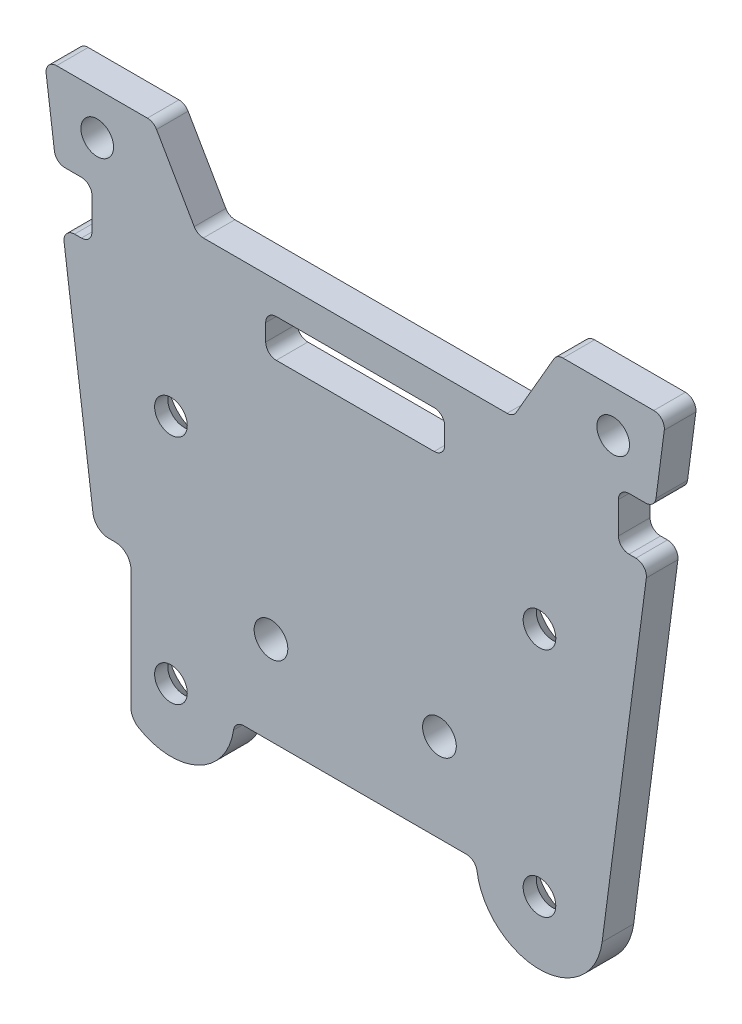
SolidWorks part; units mm, degrees
material "Thornel Mat VMA"
ref_plane "前视基准面" through (0, 0, 0) normal (0, 0, 1) x (1, 0, 0)
ref_plane "上视基准面" through (0, 0, 0) normal (0, 1, 0) x (1, 0, 0)
ref_plane "右视基准面" through (0, 0, 0) normal (1, 0, 0) x (0, 0, -1)
sketch "草图1" plane through (0, 0, 0) normal (0, 0, 1) x (1, 0, 0)
  line L0 (-37.3704, 16.5) -> (37.8879, 16.5) construction
  line L1 (29.5, -20.5) -> (18.6276, -20.5) construction
  line L2 (29.5, -20.5) -> (29.5, 20.5) construction
  line L3 (29.5, 20.5) -> (19.1569, 20.5)
  line L4 (-29.5, -20.5) -> (-29.5, 20.5) construction
  line L5 (29.5, -20.5) -> (-29.5, 20.5) construction
  line L6 (29.5, 20.5) -> (-29.5, -20.5) construction
  line L7 (0, 0) -> (16.279, 0) construction
  line L8 (-37.3704, -16.5) -> (37.8879, -16.5) construction
  line L9 (0, 0) -> (0, 13.3) construction
  line L10 (-18.6276, -20.5) -> (-29.5, -20.5) construction
  line L12 (-17.5, -24.9) -> (-17.5, -2.9) construction
  line L13 (29.5, 20.5) -> (23.4491, -25.6795)
  line L14 (-29.5, 20.5) -> (-23.4491, -25.6795)
  line L28 (-8.5, 10.3) -> (8.5, 10.3)
  line L37 (-19.1569, 20.5) -> (-15, 13.3)
  line L42 (-8.5, 10.3) -> (-8.5, 6.7)
  line L43 (-8.5, 6.7) -> (8.5, 6.7)
  line L44 (-15, 13.3) -> (15, 13.3)
  line L45 (15, 13.3) -> (19.1569, 20.5)
  line L46 (-19.1569, 20.5) -> (-29.5, 20.5)
  line L47 (11.5, -24.9) -> (-11.5, -24.9)
  line L48 (8.5, 10.3) -> (8.5, 6.7)
  line L49 (-8.5, 10.3) -> (8.5, 6.7) construction
  line L50 (-8.5, 6.7) -> (8.5, 10.3) construction
  circle A0 centre (-24.5, 16.5) radius 1.55
  circle A1 centre (-8, -16.5) radius 1.6
  circle A2 centre (8, -16.5) radius 1.6
  circle A3 centre (24.5, 16.5) radius 1.55
  circle A4 centre (-17.5, -24.9) radius 1.55
  circle A5 centre (17.5, -24.9) radius 1.55
  arc A7 (-23.4491, -25.6795) -> (-11.5, -24.9) centre (-17.5, -24.9) ccw
  circle A8 centre (-17.5, -2.9) radius 1.55
  circle A9 centre (17.5, -2.9) radius 1.55
  arc A10 (11.5, -24.9) -> (23.4491, -25.6795) centre (17.5, -24.9) ccw
  point P0 (0, 0)
  point P36 (0, 8.5)
  dimension "D3" = 16
  dimension "D5" = 3.1
  dimension "D6" = 3.2
  dimension "D9" = 3.1
  dimension "D10" = 6
  dimension "D1" = 33
  dimension "D2" = 49
  dimension "D4" = 5
  dimension "D7" = 4
  dimension "D8" = 35
  dimension "D11" = 22
  dimension "D12" = 120
  dimension "D13" = 17
  dimension "D14" = 3.6
  dimension "D15" = 8
  dimension "D19" = 3.2
  dimension "D20" = 30
  dimension "D21" = 8.4
extrude "凸台-拉伸1" add sketch "草图1" along normal blind 3
hole_wizard "打孔尺寸(%根据十字)槽沉头木螺钉的类型1" positions "3D草图1" profile "草图2" countersink size "M3" standard "GB" end condition through all
sketch3d "3D草图1"
  line L0 (-17.5, -24.9, 3) -> (-17.5, -24.9, 0) construction
  line L3 (17.5, -2.9, 3) -> (17.5, -2.9, 0) construction
  line L4 (-17.5, -2.9, 3) -> (-17.5, -2.9, 0) construction
  circle A1 centre (17.5, -24.9, 0) radius 1.55 construction
  point P0 (-17.5, -24.9, 0)
  point P10 (17.5, -2.9, 0)
  point P14 (-17.5, -2.9, 0)
  point P18 (17.5, -24.9, 0)
  point P28 (17.5, -24.9, 1.55)
sketch "草图2" plane through (-17.5, -24.9, 0) normal (1, 0, 0) x (0, 1, 0)
  line L0 (0, 0) -> (0, 3)
  line L1 (0, 3) -> (1.55, 3)
  line L2 (1.55, 3) -> (1.55, 1.75)
  line L3 (1.55, 1.75) -> (3.3, 0)
  line L5 (3.3, 0) -> (0, 0)
  line L6 (-1.55, 1.75) -> (-3.3, 0) construction
  line L11 (0, -6.35) -> (0, 107.95) construction
  dimension "通孔孔直径" = 3.1
  dimension "通孔孔深度" = 3
  dimension "近端锥形沉头孔直径" = 6.6
  dimension "近端锥形沉头孔角度" = 90
sketch "草图3" plane through (0, 0, 3) normal (0, 0, 1) x (1, 0, 0)
  line L1 (25, 12.5) -> (34, 12.5)
  line L2 (25, 12.5) -> (25, 7.5)
  line L3 (25, 7.5) -> (34, 7.5)
  line L4 (34, 12.5) -> (34, 7.5)
  line L5 (25, 12.5) -> (34, 7.5) construction
  line L6 (25, 7.5) -> (34, 12.5) construction
  line L7 (0, 0) -> (0, 20.0947) construction
  line L8 (-25, 7.5) -> (-34, 7.5)
  line L9 (-34, 12.5) -> (-34, 7.5)
  line L10 (-25, 12.5) -> (-34, 12.5)
  line L11 (-25, 12.5) -> (-25, 7.5)
  line L12 (-29.5, 7.5) -> (-29.5, 10.3094) construction
  circle A0 centre (24.5, 16.5) radius 1.55 construction
  point P0 (29.5, 10)
  dimension "D1" = 6.5
  dimension "D2" = 5
  dimension "D3" = 9
  dimension "D4" = 59
extrude "切除-拉伸1" cut sketch "草图3" against normal blind 10
fillet "圆角1" radius 1 20 edges at (-19.1569, 20.5, 1.5) (-29.5, 20.5, 1.5) (29.5, 20.5, 1.5) (-15, 13.3, 1.5) (11.5, -24.9, 1.5) (-11.5, -24.9, 1.5) (15, 13.3, 1.5) (19.1569, 20.5, 1.5) (-8.5, 10.3, 1.5) (-8.5, 6.7, 1.5) (8.5, 6.7, 1.5) (8.5, 10.3, 1.5) (27.7966, 7.5, 1.5) (-27.7966, 7.5, 1.5) (-25, 7.5, 1.5) (-25, 12.5, 1.5) (-28.4518, 12.5, 1.5) (25, 12.5, 1.5) (25, 7.5, 1.5) (28.4518, 12.5, 1.5)
sketch "草图4" plane through (0, 0, 0) normal (0, 0, -1) x (-1, 0, 0)
  line L0 (21.3, -30.9) -> (21.3, -15.9)
  line L1 (21.3, -15.9) -> (37.8655, -15.9)
  line L2 (37.8655, -15.9) -> (37.8655, -30.9)
  line L3 (37.8655, -30.9) -> (21.3, -30.9)
  line L4 (10.5718, -24.9) -> (-10.5718, -24.9) construction
  circle A2 centre (17.5, -24.9) radius 1.55 construction
  dimension "D2" = 3.8
  dimension "D1" = 6
  dimension "D3" = 15
extrude "切除-拉伸2" cut sketch "草图4" against normal blind 10
fillet "圆角2" radius 1.5 3 edges at (-24.7305, -15.9, 1.5) (-21.3, -15.9, 1.5) (-21.3, -29.5433, 1.5)
